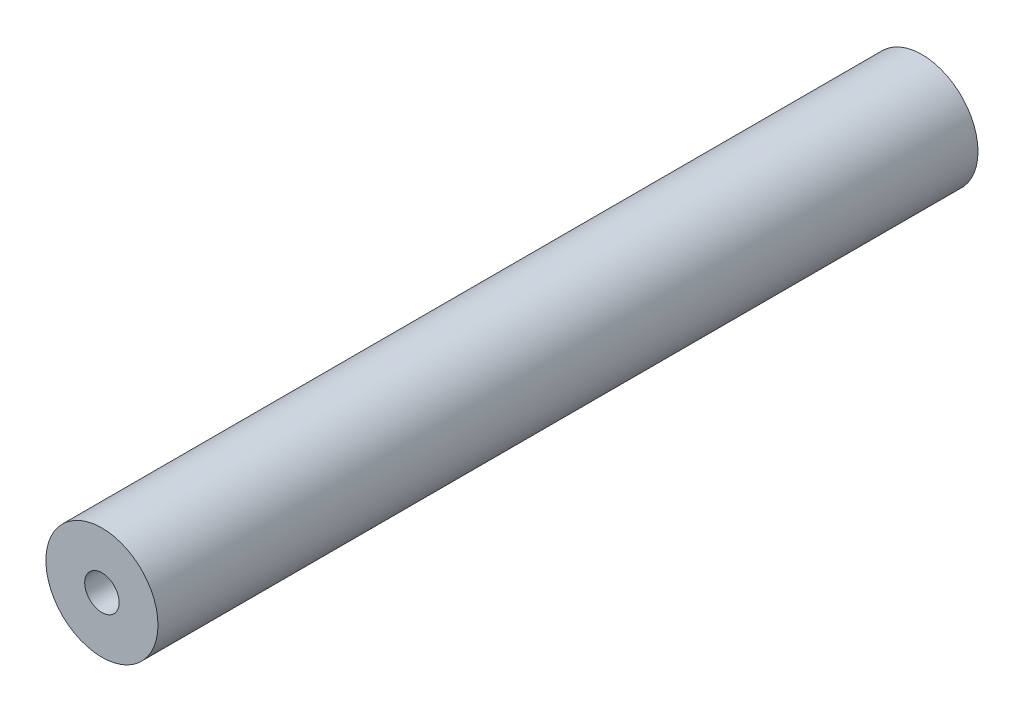
SolidWorks part; units mm, degrees
ref_plane "Alzado" through (0, 0, 0) normal (0, 0, 1) x (1, 0, 0)
ref_plane "Planta" through (0, 0, 0) normal (0, 1, 0) x (1, 0, 0)
ref_plane "Vista lateral" through (0, 0, 0) normal (1, 0, 0) x (0, 0, -1)
sketch "Croquis1" plane through (0, 0, 0) normal (0, 0, 1) x (1, 0, 0)
  circle A0 centre (0, 0) radius 0.63
  circle A1 centre (0, 0) radius 2.05
  dimension "D1" = 4.1
  dimension "D2" = 1.26
extrude "Saliente-Extruir1" add sketch "Croquis1" along normal blind 30
equation "\"k\"= 52.6246"
equation "\"A_ALETA\"= ( ( ( tan ( \"ANG_ALETA\" ) ) * \"L_ALETA\" ) + \"A_BASE\" )"
equation "\"A_BASE\"= ( \"L_DIE\" - \"E_CAJA\" )"
equation "\"L_ALETA\"=90.000000"
equation "\"TAU_ALETA\"= ( \"L_ALETA\" / ( log ( ( \"A_ALETA\" ) + 1 ) ) )"
equation "\"E_ALETA\"=5.5"
equation "\"R_SONDA\"= 2.05"
equation "\"D_SONDA\"=20.000000"
equation "\"L_CAJA\"=25.000000"
equation "\"E_CAJA\"= 2.5"
equation "\"A_CAJA\"= ( 2 * \"A_BASE\" ) + \"GAP_ALETAS\""
equation "\"W_CAJA\"= \"A_CAJA\" * \"CONST_CAJA\""
equation "\"W_CONC\"= ( \"W_CAJA\" / \"CONST_CONC\" ) "
equation "\"A_CONC\"= ( \"A_CAJA\" / \"CONST_CONC\" )"
equation "\"L_CONC\"= \"D_SONDA\" - \"OFFSET_CONC\""
equation "\"W_ALETA\"=70.000000"
equation "\"L_DIE_SONDA\"= ( \"GAP_ALETAS\" / 4 )"
equation "\"GAP_ALETAS\"=2"
equation "\"D1@Saliente-Extruir1\" = \"L_DIE\" + \"ALARGUE\""
equation "\"CONST_CONC\"=2.000000"
equation "\"K\"= 1.5"
equation "\"L_DIE\"= 15"
equation "\"L_CI\"= 18"
equation "\"CONST_CAJA\"=2.000000"
equation "\"ANG_ALETA\"=15.000000"
equation "\"R_C_SONDA\"= 0.63"
equation "\"D2@Croquis1\"=\"R_C_SONDA\"*2"
equation "\"D1@Croquis1\"=\"R_SONDA\"*2"
equation "\"TOLERANCIA\"= 0.5"
equation "\"OFFSET_CONC\"= ( 2 * \"R_TORNILLO\" )"
equation "\"R_TORNILLO\"=2.600000"
equation "\"ALARGUE\"=15"
